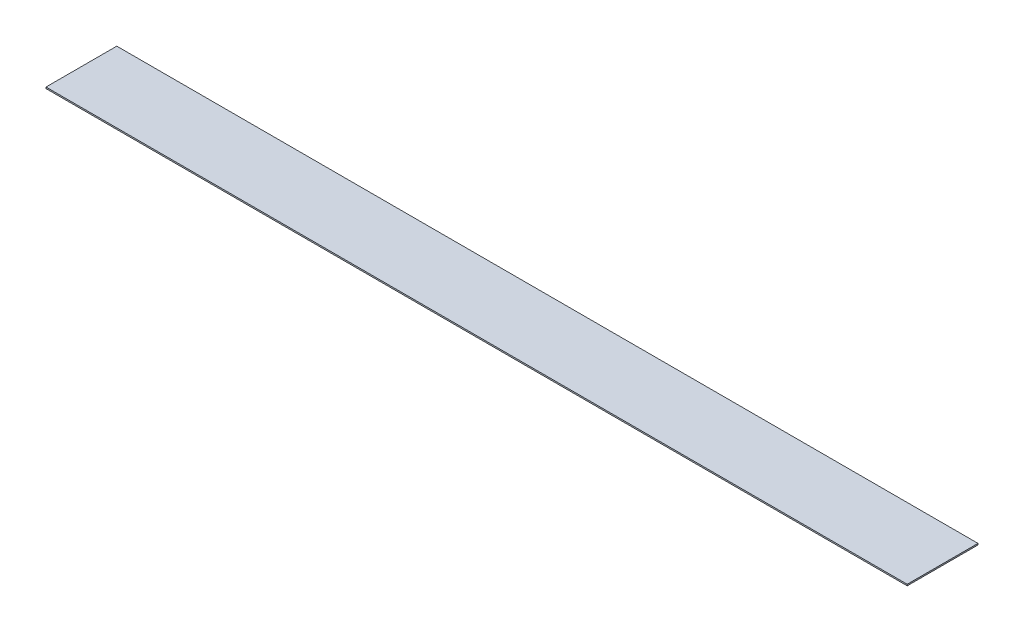
SolidWorks part; units mm, degrees
ref_plane "Front Plane" through (0, 0, 0) normal (0, 0, 1) x (1, 0, 0)
ref_plane "Top Plane" through (0, 0, 0) normal (0, 1, 0) x (1, 0, 0)
ref_plane "Right Plane" through (0, 0, 0) normal (1, 0, 0) x (0, 0, -1)
sketch "Sketch1" plane through (0, 0, 0) normal (0, 1, 0) x (1, 0, 0)
  line L1 (0, 0) -> (1825, 0)
  line L2 (0, 0) -> (0, 150)
  line L3 (0, 150) -> (1825, 150)
  line L4 (1825, 0) -> (1825, 150)
  dimension "D1" = 1825
  dimension "D2" = 150
extrude "Boss-Extrude1" add sketch "Sketch1" along normal blind 3
equation "\"boxWidth\"=1930.0"
equation "\"D1@Sketch1\"= \"indoorHeight\" + \"indoorHeight_para\" - 90 - 50"
equation "\"start\"=700.0"
equation "\"CarBeamWidth\"=700.0"
equation "\"WheelWidth\"=650.0"
equation "\"Wheel_FrontBoxDistance\"=1390.0"
equation "\"boxLength\"=5100.0"
equation "\"MetalSheet_3mm_length\"=5030.0"
equation "\"MetalSheet_3mm_width\"=1923.0"
equation "\"MetalSheet_3mm_FloorCut_L_length\"=1764.0"
equation "\"MetalSheet_3mm_FloorCut_L_disdance\"=1665.0"
equation "\"MetalSheet_3mm_FloorCut_R_length\"=1764.0"
equation "\"MetalSheet_3mm_FloorCut_R_disdance\"=1665.0"
equation "\"indoorHeight\"=1940.0"
equation "\"indoorHeight_para\"=25.0"
equation "\"rearLightHeight_para\"=265.0"
equation "\"doorColumnBar_A_FR_3mm_length_Cut\"=2310.0"
equation "\"A\"=0.0"
equation "\"haveDoor_R\"=1"
equation "\"side_door_bottom_R_3mm_length\"=1934.0"
equation "\"side_door_bottom_R_3mm_toFrontDistance\"=1583.0"
equation "\"1Bar_Side_RF_3mm_length\"=1493.0"
equation "\"1Bar_Side_RB_3mm_length\"=1493.0"
equation "\"DoorSeparator_RF_3mm_withHinge_toFrontDistance\"=1673.0"
equation "\"DoorSeparator_RF_3mm_withHinge_exist\"=1"
equation "\"DoorSeparator_RB_3mm_withHinge_toFrontDistance\"=3427.0"
equation "\"DoorSeparator_RB_3mm_withHinge_exist\"=1"
equation "\"Door_R1_L_open_Single_toFrontDistance\"=2547.5"
equation "\"Door_R1_L_open_Single_exist\"=1"
equation "\"door_base_long7_R1_L_open_Single_height\"=1890.0"
equation "\"door_base_short7_R1_L_open_Single_height\"=1890.0"
equation "\"door_base_short7_R1_L_open_Single_width\"=864"
equation "\"Door_R1_R_open_Single_toFrontDistance\"=3422.0"
equation "\"Door_R1_R_open_Single_exist\"=1"
equation "\"door_base_long7_R1_R_open_Single_height\"=1890.0"
equation "\"door_base_short7_R1_R_open_Single_height\"=1890.0"
equation "\"door_base_short7_R1_R_open_Single_width\"=864"
equation "\"x\"=66.0"
equation "\"door_base_double_BL_height\"=1890.0"
equation "\"door_base_short7_BL_Single_height\"=1890.0"
equation "\"door_base_short7_BL_Single_width\"=864"
equation "\"door_base_long7_BR_Single_height\"=1890.0"
equation "\"door_base_short7_BR_Single_height\"=1890.0"
equation "\"door_base_short7_BR_Single_width\"=864"
equation "\"da\"=62.0"
equation "\"SquareTube_length\"=1923.0"
equation "\"channelSteel_length\"=5030.0"
equation "\"SquareTube_inFront_AvgDistance\"=285.0"
equation "\"SquareTube_inFront_TotalCount\"=5"
equation "\"SquareTube_inFront1_cutDepth50_R\"=0.5"
equation "\"SquareTube_inFront1_cutDepth50_L\"=0.5"
equation "\"SquareTube_inFront2_cutDepth50_R\"=0.5"
equation "\"SquareTube_inFront2_cutDepth50_L\"=0.5"
equation "\"SquareTube_inFront3_cutDepth50_R\"=0.5"
equation "\"SquareTube_inFront3_cutDepth50_L\"=0.5"
equation "\"SquareTube_inFront4_cutDepth50_R\"=0.5"
equation "\"SquareTube_inFront4_cutDepth50_L\"=0.5"
equation "\"SquareTube_inFront5_cutDepth50_R\"=50"
equation "\"SquareTube_inFront5_cutDepth50_L\"=50"
equation "\"SquareTube_inFront6_cutDepth50_R\"=50"
equation "\"SquareTube_inFront6_cutDepth50_L\"=50"
equation "\"SquareTube_inFront7_cutDepth50_R\"=50"
equation "\"SquareTube_inFront7_cutDepth50_L\"=50"
equation "\"SquareTube_inFront8_cutDepth50_R\"=50"
equation "\"SquareTube_inFront8_cutDepth50_L\"=50"
equation "\"SquareTube_inFront9_cutDepth50_R\"=50"
equation "\"SquareTube_inFront9_cutDepth50_L\"=50"
equation "\"SquareTube_inFront10_cutDepth50_R\"=50"
equation "\"SquareTube_inFront10_cutDepth50_L\"=50"
equation "\"SquareTube_inFront11_cutDepth50_R\"=50"
equation "\"SquareTube_inFront11_cutDepth50_L\"=50"
equation "\"SquareTube_inFront12_cutDepth50_R\"=50"
equation "\"SquareTube_inFront12_cutDepth50_L\"=50"
equation "\"SquareTube_inFront13_cutDepth50_R\"=50"
equation "\"SquareTube_inFront13_cutDepth50_L\"=50"
equation "\"SquareTube_inFront14_cutDepth50_R\"=50"
equation "\"SquareTube_inFront14_cutDepth50_L\"=50"
equation "\"SquareTube_inBack_AvgDistance\"=333.125"
equation "\"SquareTube_inBack_TotalCount\"=9"
equation "\"SquareTube_inBack1_cutDepth50_R\"=50"
equation "\"SquareTube_inBack1_cutDepth50_L\"=50"
equation "\"SquareTube_inBack2_cutDepth50_R\"=50"
equation "\"SquareTube_inBack2_cutDepth50_L\"=50"
equation "\"SquareTube_inBack3_cutDepth50_R\"=50"
equation "\"SquareTube_inBack3_cutDepth50_L\"=50"
equation "\"SquareTube_inBack4_cutDepth50_R\"=50"
equation "\"SquareTube_inBack4_cutDepth50_L\"=50"
equation "\"SquareTube_inBack5_cutDepth50_R\"=50"
equation "\"SquareTube_inBack5_cutDepth50_L\"=50"
equation "\"SquareTube_inBack6_cutDepth50_R\"=0.5"
equation "\"SquareTube_inBack6_cutDepth50_L\"=0.5"
equation "\"SquareTube_inBack7_cutDepth50_R\"=0.5"
equation "\"SquareTube_inBack7_cutDepth50_L\"=0.5"
equation "\"SquareTube_inBack8_cutDepth50_R\"=0.5"
equation "\"SquareTube_inBack8_cutDepth50_L\"=0.5"
equation "\"doorColumnBar_A_FL_3mm_length_Cut\"=2310.0"
equation "\"B\"=0.0"
equation "\"haveDoor_L\"=1"
equation "\"side_door_bottom_L_3mm_length\"=1934.0"
equation "\"side_door_bottom_L_3mm_toFrontDistance\"=1583.0"
equation "\"1Bar_Side_LF_3mm_length\"=1493.0"
equation "\"1Bar_Side_LB_3mm_length\"=1493.0"
equation "\"DoorSeparator_LF_3mm_withHinge_toFrontDistance\"=1673.0"
equation "\"DoorSeparator_LF_3mm_withHinge_exist\"=1"
equation "\"DoorSeparator_LB_3mm_withHinge_toFrontDistance\"=3427.0"
equation "\"DoorSeparator_LB_3mm_withHinge_exist\"=1"
equation "\"Door_L1_L_open_Single_toFrontDistance\"=3422.0"
equation "\"Door_L1_L_open_Single_exist\"=1"
equation "\"door_base_long7_L1_L_open_Single_height\"=1890.0"
equation "\"door_base_short7_L1_L_open_Single_height\"=1890.0"
equation "\"door_base_short7_L1_L_open_Single_width\"=864"
equation "\"Door_L1_R_open_Single_toFrontDistance\"=2547.5"
equation "\"Door_L1_R_open_Single_exist\"=1"
equation "\"door_base_long7_L1_R_open_Single_height\"=1890.0"
equation "\"door_base_short7_L1_R_open_Single_height\"=1890.0"
equation "\"door_base_short7_L1_R_open_Single_width\"=864"
